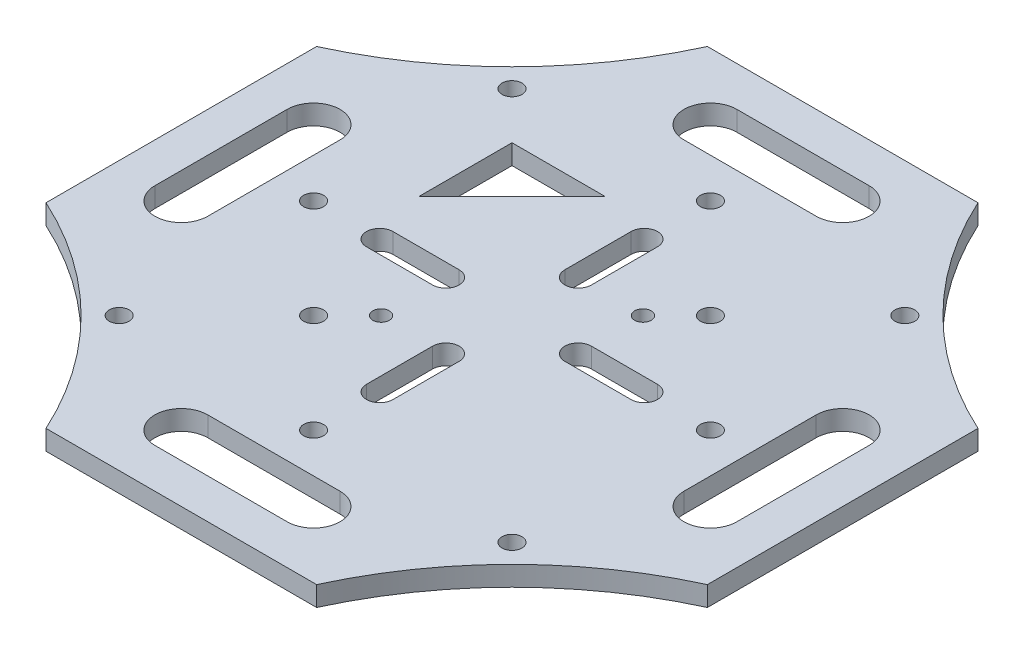
SolidWorks part; units mm, degrees
ref_plane "前视基准面" through (0, 0, 0) normal (0, 0, 1) x (1, 0, 0)
ref_plane "上视基准面" through (0, 0, 0) normal (0, 1, 0) x (1, 0, 0)
ref_plane "右视基准面" through (0, 0, 0) normal (1, 0, 0) x (0, 0, -1)
sketch "草图1" plane through (0, 0, 0) normal (0, 1, 0) x (1, 0, 0)
  line L0 (0, 0) -> (0, 75)
  line L1 (0, 0) -> (75, 0)
  line L2 (0, 0) -> (0, -75)
  line L3 (0, 0) -> (-75, 0)
  line L4 (0, 75) -> (15, 75)
  line L5 (0, 75) -> (-15, 75)
  line L6 (75, 0) -> (75, 15)
  line L7 (75, 0) -> (75, -15)
  line L8 (0, -75) -> (15, -75)
  line L9 (0, -75) -> (-15, -75)
  line L10 (-75, 0) -> (-75, -15)
  line L11 (-75, 0) -> (-75, 15)
  line L12 (75, 0) -> (70, 0)
  arc A0 (-75, 15) -> (-15, 75) centre (-75, 75) ccw
  arc A1 (15, 75) -> (75, 15) centre (75, 75) ccw
  arc A2 (75, -15) -> (15, -75) centre (75, -75) ccw
  arc A3 (-15, -75) -> (-75, -15) centre (-75, -75) ccw
  circle A4 centre (-11, 70) radius 1.25
  circle A5 centre (11, 70) radius 1.25
  circle A6 centre (70, -11) radius 1.25
  circle A7 centre (70, 11) radius 1.25
  circle A8 centre (-11, -70) radius 1.25
  circle A9 centre (11, -70) radius 1.25
  circle A10 centre (-70, 11) radius 1.25
  circle A11 centre (-70, -11) radius 1.25
  point P9 (0, 0)
  point P21 (0, 0)
  point P32 (0, 0)
  point P35 (0, 0)
  point P44 (0, 0)
  dimension "D1" = 4
extrude "凸台-拉伸1" add sketch "草图1" along normal blind 3 contours A2 L7 L1 L2 L8 A9 A6 | A3 L9 L2 L3 L10 A11 A8 | A0 L11 L3 L0 L5 A4 A10 | A1 L4 L0 L1 L6 A7 A5
sketch "草图2" plane through (0, 0, 0) normal (0, -1, 0) x (1, 0, 0)
  line L0 (0, 0) -> (-32.5736, -32.5736)
  line L1 (0, 0) -> (32.5736, -32.5736)
  line L2 (-31.4663, 0.3536) -> (-0.3536, 31.4663)
  line L3 (31.4663, -0.3536) -> (-0.3536, 31.4663)
  line L4 (0.3536, -31.4663) -> (31.4663, -0.3536)
  line L5 (0.3536, -31.4663) -> (-31.4663, 0.3536)
  arc A0 (-15, -75) -> (-75, -15) centre (-75, -75) ccw construction
  circle A2 centre (0.3536, -31.4663) radius 1.5
  circle A3 centre (31.4663, -0.3536) radius 1.5
  circle A4 centre (-0.3536, 31.4663) radius 1.5
  circle A5 centre (-31.4663, 0.3536) radius 1.5
  point P12 (-15.5563, -15.5563)
  point P16 (-15.9099, 15.9099)
  point P17 (15.9099, -15.9099)
extrude "切除-拉伸1" cut sketch "草图2" against normal blind 3 contours A3 | A2 | A5 | A4
sketch "草图3" plane through (0, 3, 0) normal (0, 1, 0) x (1, 0, 0)
  line L0 (0.3536, 31.4663) -> (-31.4663, -0.3536)
  line L1 (-15.5563, 15.5563) -> (-22.6274, 22.6274)
  line L2 (-15.5563, 15.5563) -> (-12.0208, 19.0919)
  line L3 (-15.5563, 15.5563) -> (-19.0919, 12.0208)
  line L4 (-19.0919, 12.0208) -> (-22.6274, 22.6274)
  line L5 (-12.0208, 19.0919) -> (-22.6274, 22.6274)
extrude "切除-拉伸2" cut sketch "草图3" against normal blind 3 contours L0 L5 L1 | L4 L0 L1
sketch "草图4" plane through (0, 3, 0) normal (0, 1, 0) x (1, 0, 0)
  line L0 (31.4663, 0.3536) -> (-0.3536, -31.4663)
  line L1 (0, 0) -> (21.2132, -21.2132)
  line L2 (28.2843, -14.1421) -> (14.1421, -28.2843)
  line L3 (14.1421, -28.2843) -> (28.2843, -14.1421) construction
  line L4 (8.4817, -22.6239) -> (22.6239, -8.4817)
  line L5 (19.8025, -33.9447) -> (33.9447, -19.8025)
  arc A0 (8.4817, -22.6239) -> (19.8025, -33.9447) centre (14.1421, -28.2843) ccw
  arc A1 (33.9447, -19.8025) -> (22.6239, -8.4817) centre (28.2843, -14.1421) ccw
  point P9 (21.2132, -21.2132)
extrude "切除-拉伸3" cut sketch "草图4" against normal blind 3
sketch "草图5" plane through (0, 3, 0) normal (0, 1, 0) x (1, 0, 0)
  line L0 (-12.0208, 19.0919) -> (-8.4853, 22.6274)
  line L1 (-8.4853, 22.6274) -> (-22.6274, 22.6274)
  line L2 (-19.0919, 12.0208) -> (-22.6274, 8.4853)
  line L3 (-22.6274, 8.4853) -> (-22.6274, 22.6274)
  line L4 (-12.0208, 19.0919) -> (-22.6274, 22.6274)
  line M28 (-19.0919, 12.0208) -> (-22.6274, 22.6274)
extrude "切除-拉伸4" cut sketch "草图5" against normal blind 10 contours L3 L2 M28 | L4 L0 L1
sketch "草图6" plane through (0, 3, 0) normal (0, 1, 0) x (1, 0, 0)
  line L0 (0, 0) -> (-28.2843, -28.2843)
  line L1 (-28.2843, -28.2843) -> (-35.3553, -21.2132)
  line L2 (0, 0) -> (-22.6274, 22.6274)
  circle A0 centre (-35.3553, -21.2132) radius 1.5
  circle A1 centre (-21.2132, -35.3553) radius 1.5
  circle A2 centre (35.3553, 21.2132) radius 1.5
  circle A3 centre (21.2132, 35.3553) radius 1.5
extrude "切除-拉伸5" cut sketch "草图6" against normal blind 10 contours A1 | A0 | A2 | A3
sketch "草图7" plane through (0, 3, 0) normal (0, 1, 0) x (1, 0, 0)
  circle A0 centre (-29.6985, 29.6985) radius 1.5
  circle A1 centre (29.6985, 29.6985) radius 1.5
  circle A2 centre (29.6985, -29.6985) radius 1.5
  circle A3 centre (-29.6985, -29.6985) radius 1.5
  point P11 (0, 0)
  dimension "D1" = 4
extrude "切除-拉伸8" cut sketch "草图7" against normal blind 10
sketch "草图8" plane through (0, 3, 0) normal (0, 1, 0) x (1, 0, 0)
  circle A0 centre (-11, 55) radius 1.5
  circle A1 centre (11, 55) radius 1.5
  circle A2 centre (55, 11) radius 1.5
  circle A3 centre (55, -11) radius 1.5
  circle A4 centre (11, -55) radius 1.5
  circle A5 centre (-11, -55) radius 1.5
  circle A6 centre (-55, -11) radius 1.5
  circle A7 centre (-55, 11) radius 1.5
  point P21 (0, 0)
  dimension "D1" = 4
extrude "切除-拉伸9" cut sketch "草图8" against normal blind 10
sketch "草图9" plane through (0, 3, 0) normal (0, 1, 0) x (1, 0, 0)
  circle A0 centre (0, 0) radius 15
extrude "切除-拉伸10" cut sketch "草图9" against normal blind 10
sketch "草图11" plane through (0, 3, 0) normal (0, 1, 0) x (1, 0, 0)
  circle A0 centre (-35.3553, -21.2132) radius 1.5
  circle A2 centre (35.3553, 21.2132) radius 1.5
  circle A3 centre (21.2132, 35.3553) radius 1.5
  circle A4 centre (0.3536, 31.4663) radius 1.5
  circle A5 centre (31.4663, 0.3536) radius 1.5
  circle A6 centre (-0.3536, -31.4663) radius 1.5
  circle A7 centre (-31.4663, -0.3536) radius 1.5
  circle A8 centre (-21.2132, -35.3553) radius 1.5
extrude "凸台-拉伸3" add sketch "草图11" against normal blind 3
sketch "草图12" plane through (0, 3, 0) normal (0, 1, 0) x (1, 0, 0)
  line L0 (0, 0) -> (-40, 0)
  line L1 (-40, 0) -> (-40, 10)
  line L2 (-40, 0) -> (-40, -10)
  line L3 (-40, -10) -> (-40, 10) construction
  line L4 (-44, -10) -> (-44, 10)
  line L5 (-36, -10) -> (-36, 10)
  line L6 (-10, 40) -> (10, 40) construction
  line L7 (-10, 44) -> (10, 44)
  line L8 (-10, 36) -> (10, 36)
  line L9 (40, 10) -> (40, -10) construction
  line L10 (44, 10) -> (44, -10)
  line L11 (36, 10) -> (36, -10)
  line L12 (10, -40) -> (-10, -40) construction
  line L13 (10, -44) -> (-10, -44)
  line L14 (10, -36) -> (-10, -36)
  arc A0 (-44, -10) -> (-36, -10) centre (-40, -10) ccw
  arc A1 (-36, 10) -> (-44, 10) centre (-40, 10) ccw
  arc A2 (-10, 44) -> (-10, 36) centre (-10, 40) ccw
  arc A3 (10, 36) -> (10, 44) centre (10, 40) ccw
  arc A4 (44, 10) -> (36, 10) centre (40, 10) ccw
  arc A5 (36, -10) -> (44, -10) centre (40, -10) ccw
  arc A6 (10, -44) -> (10, -36) centre (10, -40) ccw
  arc A7 (-10, -36) -> (-10, -44) centre (-10, -40) ccw
  point P3 (-40, 0)
  point P13 (0, 40)
  point P20 (40, 0)
  point P27 (0, -40)
  point P34 (0, 0)
  dimension "D1" = 4
extrude "切除-拉伸12" cut sketch "草图12" against normal blind 3
sketch "草图14" plane through (0, 3, 0) normal (0, 1, 0) x (1, 0, 0)
  line L0 (22.8277, -8.285) -> (8.285, -22.8277) construction
  line L1 (19.8025, -33.9447) -> (33.9447, -19.8025) construction
  line L2 (8.285, -22.8277) -> (22.8277, -8.285)
  line L3 (22.8277, -8.285) -> (19.8025, -33.9447)
  line L4 (19.8025, -33.9447) -> (33.9447, -19.8025)
  arc A0 (8.285, -22.8277) -> (19.8025, -33.9447) centre (14.1421, -28.2843) ccw
  arc A1 (8.285, -22.8277) -> (19.8025, -33.9447) centre (14.1421, -28.2843) ccw construction
  arc A2 (33.9447, -19.8025) -> (22.8277, -8.285) centre (28.2843, -14.1421) ccw construction
  arc A3 (22.8277, -8.285) -> (32.1857, -7.1522) centre (28.2843, -14.1421) ccw
  circle A4 centre (28.2843, -14.1421) radius 8.005
extrude "凸台-拉伸4" add sketch "草图14" against normal blind 3 contours A3 A4 L3 | L2 A3 L3 | A3 L2 A0 L3 | A3 L3 L4
sketch "草图15" plane through (0, 3, 0) normal (0, 1, 0) x (1, 0, 0)
  circle A0 centre (0, 0) radius 15
extrude "凸台-拉伸5" add sketch "草图15" against normal blind 3
sketch "草图17" plane through (0, 3, 0) normal (0, 1, 0) x (1, 0, 0)
  line L0 (0, 0) -> (0, -20)
  line L1 (0, -20) -> (0, -10) construction
  line L2 (-2, -20) -> (-2, -10)
  line L3 (2, -20) -> (2, -10)
  line L4 (-20, 0) -> (-10, 0) construction
  line L5 (-20, 2) -> (-10, 2)
  line L6 (-20, -2) -> (-10, -2)
  line L7 (0, 20) -> (0, 10) construction
  line L8 (2, 20) -> (2, 10)
  line L9 (-2, 20) -> (-2, 10)
  line L10 (20, 0) -> (10, 0) construction
  line L11 (20, -2) -> (10, -2)
  line L12 (20, 2) -> (10, 2)
  arc A0 (-2, -20) -> (2, -20) centre (0, -20) ccw
  arc A1 (2, -10) -> (-2, -10) centre (0, -10) ccw
  arc A2 (-20, 2) -> (-20, -2) centre (-20, 0) ccw
  arc A3 (-10, -2) -> (-10, 2) centre (-10, 0) ccw
  arc A4 (2, 20) -> (-2, 20) centre (0, 20) ccw
  arc A5 (-2, 10) -> (2, 10) centre (0, 10) ccw
  arc A6 (20, -2) -> (20, 2) centre (20, 0) ccw
  arc A7 (10, 2) -> (10, -2) centre (10, 0) ccw
  point P3 (0, -15)
  point P13 (-15, 0)
  point P20 (0, 15)
  point P27 (15, 0)
  point P33 (0, 0)
  dimension "D1" = 4
extrude "切除-拉伸13" cut sketch "草图17" against normal blind 3 contours L8 A5 L9 A4 | L12 A7 L11 A6 | L3 A1 L2 A0 | L5 A3 L6 A2
sketch "草图18" plane through (0, 3, 0) normal (0, 1, 0) x (1, 0, 0)
  line L0 (0, 0) -> (-32.5736, 32.5736)
  line L1 (-32.5736, 32.5736) -> (-46.7157, 46.7157)
  line L2 (-50.2513, 50.2513) -> (-61.9773, 38.5252)
  line L3 (-46.7157, 46.7157) -> (-50.2513, 50.2513)
  line L4 (-61.9773, 38.5252) -> (-38.5252, 61.9773)
  line L5 (-38.5252, 61.9773) -> (-22.5002, 45.9523)
  line L6 (-61.9773, 38.5252) -> (-45.9523, 22.5002)
  arc A0 (-75, 15) -> (-15, 75) centre (-75, 75) ccw construction
  circle A1 centre (-67.9289, 67.9289) radius 30
  circle A2 centre (-75, 75) radius 60
extrude "凸台-拉伸7" add sketch "草图18" against normal blind 3 contours L4 A1 L2 | L2 A1 L3 | L3 A1 L4 | L6 A2 L1 A1 | L1 A2 L5 A1
sketch "草图19" plane through (0, 3, 0) normal (0, 1, 0) x (1, 0, 0)
  line L0 (-61.9773, 38.5252) -> (-38.5252, 61.9773)
  line L1 (-50.2513, 50.2513) -> (-36.1091, 36.1091)
  line L2 (-36.1091, 36.1091) -> (-43.1802, 29.0381)
  line L3 (-36.1091, 36.1091) -> (-29.0381, 43.1802)
  line L4 (-29.0381, 43.1802) -> (-37.1408, 51.2829)
  line L5 (-37.1408, 51.2829) -> (-51.2829, 37.1408)
  line L6 (-51.2829, 37.1408) -> (-43.1802, 29.0381)
  circle A1 centre (-67.9289, 67.9289) radius 35
  circle A2 centre (-67.9289, 67.9289) radius 45
extrude "切除-拉伸14" cut sketch "草图19" against normal blind 3 contours L1 A2 L4 A1 | L6 A2 L1 A1
sketch "草图21" plane through (0, 3, 0) normal (0, 1, 0) x (1, 0, 0)
  line L0 (-61.9773, 38.5252) -> (-38.5252, 61.9773)
  line L1 (-67.9289, 67.9289) -> (-53.7868, 53.7868)
  line L2 (-82.0711, 82.0711) -> (-75, 75)
  line L3 (-67.9289, 67.9289) -> (-82.0711, 82.0711)
  line L4 (-53.7868, 53.7868) -> (-60.8579, 60.8579)
  line L5 (-82.0711, 82.0711) -> (-75, 75) construction
  line L6 (-81.1872, 82.955) -> (-74.1161, 75.8839)
  line L7 (-82.955, 81.1872) -> (-75.8839, 74.1161)
  line L8 (-60.8579, 60.8579) -> (-53.7868, 53.7868) construction
  line L9 (-59.974, 61.7417) -> (-52.9029, 54.6707)
  line L10 (-61.7417, 59.974) -> (-54.6707, 52.9029)
  arc A0 (-81.1872, 82.955) -> (-82.955, 81.1872) centre (-82.0711, 82.0711) ccw
  arc A1 (-75.8839, 74.1161) -> (-74.1161, 75.8839) centre (-75, 75) ccw
  arc A2 (-59.974, 61.7417) -> (-61.7417, 59.974) centre (-60.8579, 60.8579) ccw
  arc A3 (-54.6707, 52.9029) -> (-52.9029, 54.6707) centre (-53.7868, 53.7868) ccw
  point P2 (-78.5355, 78.5355)
  point P15 (-57.3223, 57.3223)
extrude "切除-拉伸15" cut sketch "草图21" against normal blind 3
pattern_circular "阵列(圆周)1" count 8 over 360 about axis through (-67.9289, 0, -67.9289) along (0, 1, 0) of "切除-拉伸15"
sketch "草图22" plane through (0, 3, 0) normal (0, 1, 0) x (1, 0, 0)
  line L0 (0, 0) -> (9.8995, 9.8995)
  line L1 (0, 0) -> (-9.8995, -9.8995)
  circle A0 centre (9.8995, 9.8995) radius 1.25
  circle A1 centre (-9.8995, -9.8995) radius 1.25
extrude "切除-拉伸17" cut sketch "草图22" against normal blind 3 contours A0 | A1
sketch "草图23" plane through (0, 3, 0) normal (0, 1, 0) x (1, 0, 0)
  circle A0 centre (0, 30) radius 1.5
  circle A1 centre (30, 0) radius 1.5
  circle A2 centre (0, -30) radius 1.5
  circle A3 centre (-30, 0) radius 1.5
  point P13 (0, 0)
  dimension "D1" = 4
extrude "切除-拉伸18" cut sketch "草图23" against normal blind 10
sketch "草图24" plane through (0, 3, 0) normal (0, 1, 0) x (1, 0, 0)
  circle A0 centre (-15, -15) radius 1.5
  circle A1 centre (15, 15) radius 1.5
extrude "切除-拉伸19" cut sketch "草图24" against normal blind 10
sketch "草图25" plane through (0, 3, 0) normal (0, 1, 0) x (1, 0, 0)
  arc A0 (-15, 75) -> (-22.5002, 45.9523) centre (-75, 75) ccw
  circle A1 centre (-75, 75) radius 60
extrude "切除-拉伸21" cut sketch "草图25" against normal blind 48 contours A0 A1
sketch "草图26" plane through (0, 3, 0) normal (0, 1, 0) x (1, 0, 0)
  line L0 (0, 0) -> (-50, 0)
  line L1 (-20.4564, 50) -> (20.4564, 50)
  line L2 (-50, -20.4564) -> (-50, 20.4564)
  line L3 (-50, 20.4564) -> (-97.0628, 20.4564)
  line L4 (-50, 20.4564) -> (-50, -20.4564)
  line L5 (-50, -20.4564) -> (-97.0628, -20.4564)
  line L6 (-97.0628, 20.4564) -> (-97.0628, -20.4564)
  line L7 (20.4564, 50) -> (20.4564, 97.0628)
  line L8 (20.4564, 97.0628) -> (-20.4564, 97.0628)
  line L9 (-20.4564, 50) -> (-20.4564, 97.0628)
  line L10 (50, 20.4564) -> (50, -20.4564)
  line L11 (50, -20.4564) -> (97.0628, -20.4564)
  line L12 (97.0628, -20.4564) -> (97.0628, 20.4564)
  line L13 (50, 20.4564) -> (97.0628, 20.4564)
  line L14 (20.4564, -50) -> (-20.4564, -50)
  line L15 (-20.4564, -50) -> (-20.4564, -97.0628)
  line L16 (-20.4564, -97.0628) -> (20.4564, -97.0628)
  line L17 (20.4564, -50) -> (20.4564, -97.0628)
  arc A0 (-15, -75) -> (-75, -15) centre (-75, -75) ccw construction
  arc A1 (-75, 15) -> (-15, 75) centre (-75, 75) ccw construction
  point P28 (0, 0)
  dimension "D1" = 4
extrude "切除-拉伸22" cut sketch "草图26" against normal blind 48 contours L13 L10 L11 L12 | L9 L1 L7 L8 | L3 L6 L5 L2 | L17 L14 L15 L16
